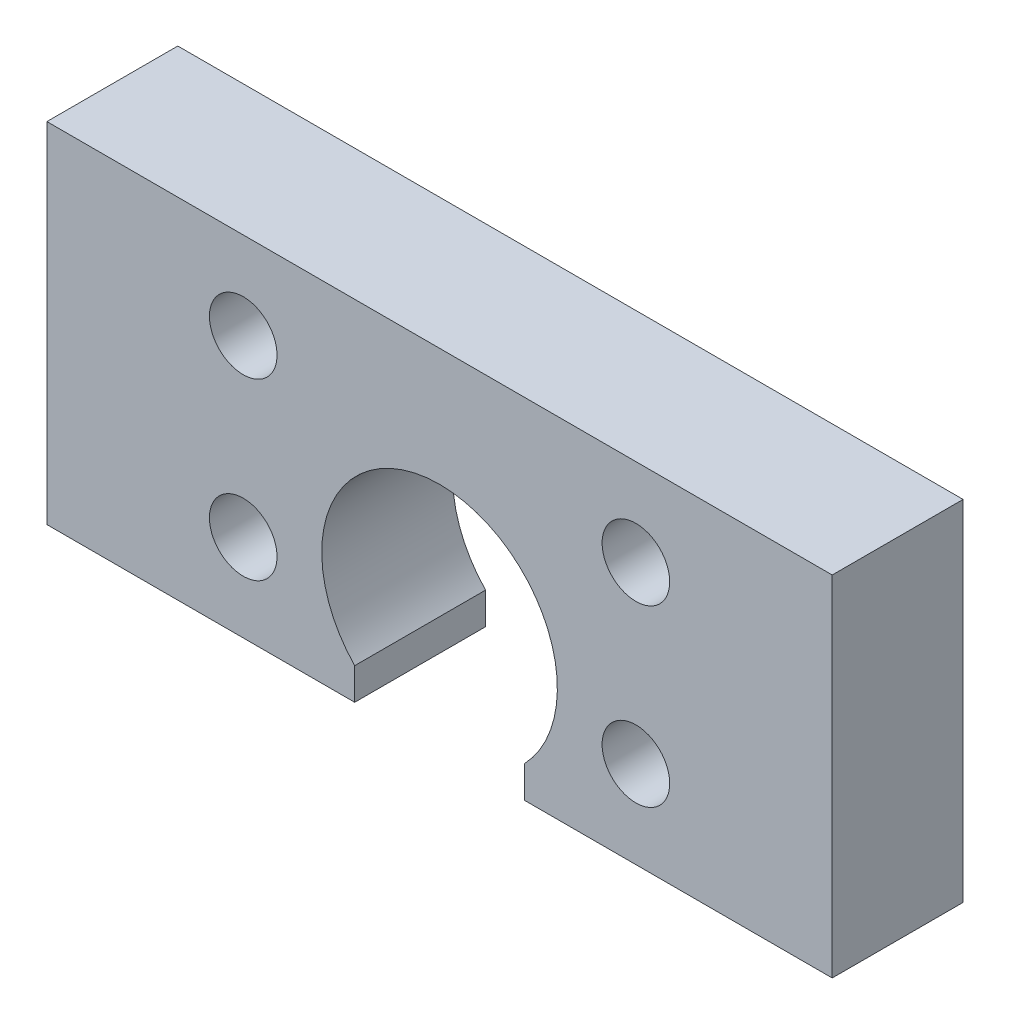
SolidWorks part; units mm, degrees
ref_plane "Płaszczyzna przednia" through (0, 0, 0) normal (0, 0, 1) x (1, 0, 0)
ref_plane "Płaszczyzna górna" through (0, 0, 0) normal (0, 1, 0) x (1, 0, 0)
ref_plane "Płaszczyzna prawa" through (0, 0, 0) normal (1, 0, 0) x (0, 0, -1)
sketch "Szkic1" plane through (0, 0, 0) normal (0, 0, 1) x (1, 0, 0)
  line L0 (71.503, 0) -> (35.503, 0)
  line L1 (71.503, 0) -> (71.503, -16)
  line L2 (35.503, 0) -> (35.503, -16)
  line L3 (71.503, -16) -> (35.503, -16)
  dimension "D1" = 36
  dimension "D2" = 16
extrude "Dodanie-wyciągnięcie1" add sketch "Szkic1" against normal blind 6
sketch "Szkic2" plane through (0, 0, 0) normal (0, 0, 1) x (1, 0, 0)
  line L0 (35.503, -16) -> (71.503, -16) construction
  line L1 (35.503, 0) -> (35.503, -16) construction
  line L2 (49.613, -14.93) -> (49.613, -16)
  line L5 (57.393, -14.93) -> (57.393, -16)
  line L6 (49.613, -16) -> (57.393, -16)
  line L7 (49.613, -14.93) -> (49.613, -14.5454)
  line L8 (57.393, -14.93) -> (57.393, -14.5454)
  arc A0 (57.393, -14.5454) -> (49.613, -14.5454) centre (53.503, -10.8) ccw
  dimension "D1" = 5.2
  dimension "D2" = 10.8
  dimension "D3" = 18
  dimension "D4" = 3.89
  dimension "D5" = 3.89
extrude "Wytnij-wyciągnięcie1" cut sketch "Szkic2" against normal blind 6
sketch "Szkic3" plane through (0, 0, -6) normal (0, 0, -1) x (-1, 0, 0)
  circle A0 centre (-44.503, -12) radius 1.55 construction
  circle A1 centre (-44.503, -4) radius 1.55 construction
  circle A2 centre (-62.503, -12) radius 1.55 construction
  circle A3 centre (-62.503, -4) radius 1.55 construction
  circle A4 centre (-44.503, -12) radius 1.55
  circle A5 centre (-44.503, -4) radius 1.55
  circle A6 centre (-62.503, -12) radius 1.55
  circle A7 centre (-62.503, -4) radius 1.55
extrude "Wytnij-wyciągnięcie2" cut sketch "Szkic3" against normal through all
